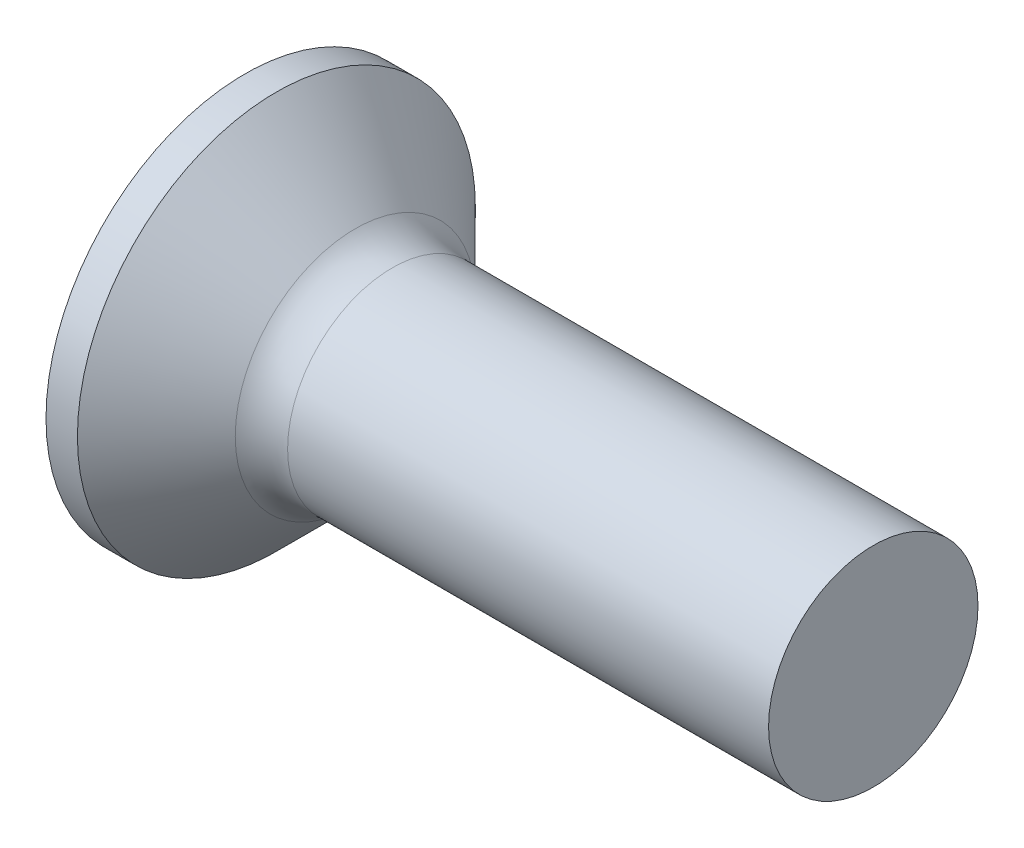
SolidWorks part; units mm, degrees
ref_plane "Plane1" through (0, 0, 0) normal (0, 0, 1) x (1, 0, 0)
ref_plane "Plane2" through (0, 0, 0) normal (0, 1, 0) x (1, 0, 0)
ref_plane "Plane3" through (0, 0, 0) normal (1, 0, 0) x (0, 0, -1)
sketch "BodySke" plane through (0, 0, 0) normal (0, 0, 1) x (1, 0, 0)
  line L0 (0, 0) -> (0, 1.9)
  line L1 (0, 1.9) -> (0.3, 1.9)
  line L2 (1.2, 1) -> (6, 1)
  line L3 (6, 1) -> (6, 0)
  line L4 (6, 0) -> (0, 0)
  line L5 (-6.35, 0) -> (82.55, 0) construction
  line L6 (1.2, -1) -> (6, -1) construction
  line L7 (0.3, -1.9) -> (1.2, -1) construction
  line L8 (0.3, 1.9) -> (1.2, 1)
  line L9 (0, -1.9) -> (0.3, -1.9) construction
  line L10 (1.6, 2.5875) -> (1.6, -6.9375) construction
  line L11 (0, 6.35) -> (0, -3.175) construction
  dimension "Diameter" = 2
  dimension "Length" = 6
  dimension "Head_ht" = 1.2
  dimension "Head_dia" = 3.8
  dimension "Head_ang" = 90
  dimension "D6" = 0.3
  dimension "Advance" = 0.4
  dimension "Thread_nom" = 6
revolve "Base-Revolve" add sketch "BodySke"
cosmetic thread "ThreadCosmetic" [suppressed]
fillet "Fillet1" radius 0.5 1 edges at (1.2, 0, 1)
sketch "Sketch3" plane through (0, 0, 0) normal (-1, 0, 0) x (0, 0, 1)
  line L0 (-0.24, 0.95) -> (0.24, 0.95)
  line L1 (0.24, 0.95) -> (0.24, -0.95)
  line L2 (0.24, -0.95) -> (-0.24, -0.95)
  line L3 (-0.24, -0.95) -> (-0.24, 0.95)
  dimension "D1" = 0.95
  dimension "Cross_dia" = 1.9
  dimension "D2" = 0.24
  dimension "Cross_width" = 0.48
ref_plane "Plane4" through (1.2, 0, 0) normal (-1, 0, 0) x (0, 0, 1)
sketch "Sketch4" plane through (1.2, 0, 0) normal (-1, 0, 0) x (0, 0, 1)
  line L0 (-0.24, 0.3517) -> (0.24, 0.3517)
  line L3 (0.24, 0.3517) -> (0.24, -0.3517)
  line L4 (0.24, -0.3517) -> (-0.24, -0.3517)
  line L5 (-0.24, -0.3517) -> (-0.24, 0.3517)
  dimension "D1" = 0.48
  dimension "D2" = 0.7034
  dimension "D3" = 0.24
  dimension "D4" = 0.3517
loft "Recess" cut profiles "Sketch3", "Sketch4"
pattern_circular "RecPat" count 2 every 90 about axis through (0, 0, 0) along (1, 0, 0) of "Recess"
sketch "RecCorSke" plane through (0, 0, 0) normal (0, 0, 1) x (1, 0, 0)
  line L0 (-3.175, 0) -> (15.875, 0) construction
  line L2 (0, 0) -> (0, 0.4394)
  line L3 (0, 0.4394) -> (1.2, 0.3555)
  line L4 (1.2, 0.3555) -> (1.3155, 0)
  line L5 (1.3155, 0) -> (0, 0)
  dimension "Diameter" = 0.711
  dimension "Depth" = 1.2
  dimension "Draft_angle" = 4
  dimension "Bottom_angle" = 18
revolve "RecessCore" cut sketch "RecCorSke" angle 360 about L0
sketch "ThdSchSke" plane through (0, 0, 0) normal (0, 0, 1) x (1, 0, 0)
  line L0 (1.6, -0.774) -> (1.4418, -1)
  line L1 (1.6, -0.774) -> (1.7582, -1)
  line L2 (1.7582, -1) -> (1.7582, -1.25)
  line L3 (-3.175, 0) -> (5.1513, 0) construction
  line L5 (1.7582, -1.25) -> (1.4418, -1.25)
  line L6 (1.4418, -1.25) -> (1.4418, -1)
  line L7 (0, 1.9) -> (0, -1.9) construction
  dimension "Thread_minor" = 1.548
  dimension "Diameter" = 2
  dimension "Start" = 1.6
  dimension "SideAngle" = 55
  dimension "VeeAngle" = 70
  dimension "Overcut" = 2.5
revolve "ThreadSchematic" [suppressed] cut sketch "ThdSchSke" angle 360 about L3
pattern_linear "ThdSchPat" [suppressed]
equation "\"D1@Sketch3\" = \"Cross_dia@Sketch3\" / 2"
equation "\"D2@Sketch3\" = \"Cross_width@Sketch3\" / 2"
equation "\"Depth@RecCorSke\" = \"Cross_depth@Plane4\""
equation "\"D1@Sketch4\" = \"Cross_width@Sketch3\""
equation "\"D2@Sketch4\" = \"Cross_dia@Sketch3\" - 2.0 * \"Cross_depth@Plane4\" * tan(26.5  * 0.017453292)"
equation "\"D3@Sketch4\" = \"D1@Sketch4\" / 2"
equation "\"D4@Sketch4\" = \"D2@Sketch4\" / 2"
equation "\"Thread_length@ThreadCosmetic\" = ((sgn( (\"Length@BodySke\" - \"Advance@BodySke\" * 1.0 - \"Head_ht@BodySke\" ) - \"Thread_nom@BodySke\" )-1)*( (\"Length@BodySke\" - \"Advance@BodySke\" * 1.0 - \"Head_ht@BodySke\" ) - \"Thread_nom@BodySke\" ))/-2+ \"Thread_nom@BodySke\""
equation "\"Thread_minor@ThdSchSke\" = \"Thread_minor@ThreadCosmetic\""
equation "\"Diameter@ThdSchSke\" = \"Diameter@BodySke\""
equation "\"Overcut@ThdSchSke\" = \"Diameter@BodySke\" * 1.25"
equation "\"Start@ThdSchSke\" = 0.000001 + \"Length@BodySke\" - \"Thread_length@ThreadCosmetic\"  '---Countersunk---"
equation "\"Num_threads@ThdSchPat\" = int( \"Thread_length@ThreadCosmetic\" / \"Advance@BodySke\" + 0.999 )  + 1"
equation "\"Advance@ThdSchPat\" = \"Thread_length@ThreadCosmetic\" /  (\"Num_threads@ThdSchPat\" - 1) 'relax it"
